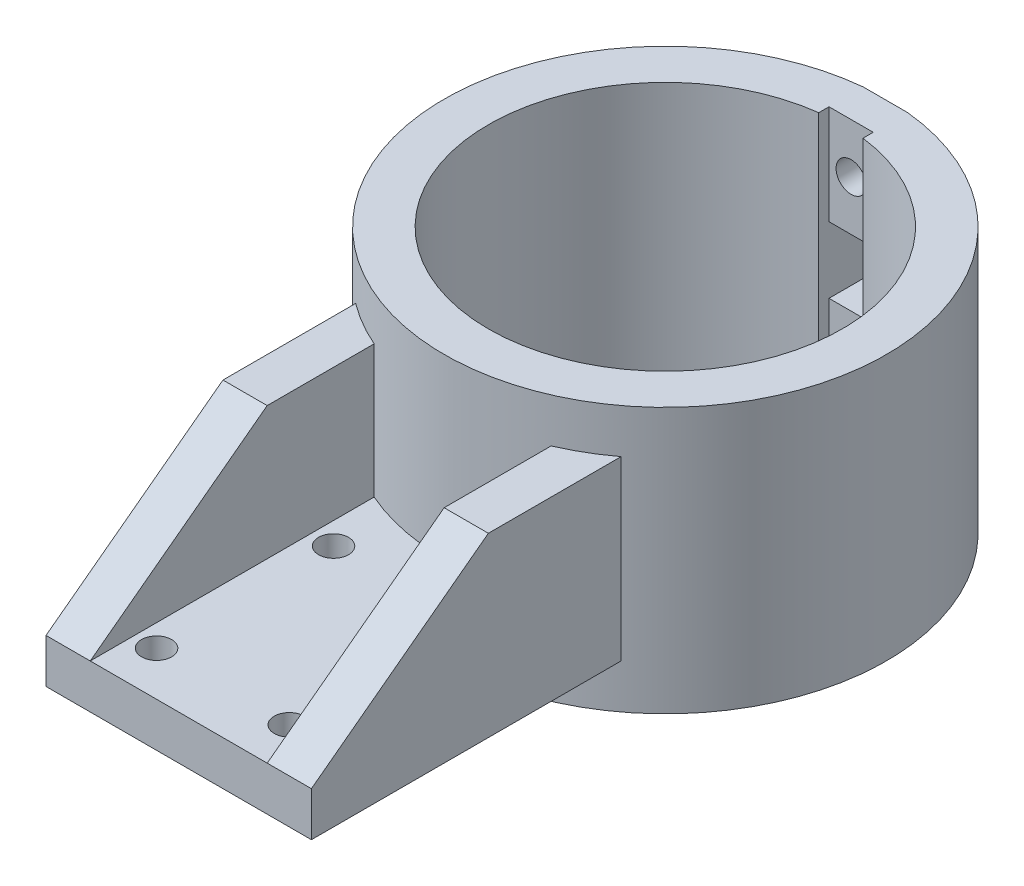
SolidWorks part; units mm, degrees
material "AISI 304"
ref_plane "前视基准面" through (0, 0, 0) normal (0, 0, 1) x (1, 0, 0)
ref_plane "上视基准面" through (0, 0, 0) normal (0, 1, 0) x (1, 0, 0)
ref_plane "右视基准面" through (0, 0, 0) normal (1, 0, 0) x (0, 0, -1)
ref_plane "Plane1" through (0, 0, 50) normal (0, 0, 1) x (1, 0, 0)
sketch "Sketch1" plane through (0, 0, 0) normal (0, 1, 0) x (1, 0, 0)
  circle A0 centre (0, 0) radius 50
  circle A1 centre (0, 0) radius 40
  dimension "D1" = 80
  dimension "D2" = 100
extrude "Extrude1" add sketch "Sketch1" along normal blind 60
sketch "Sketch2" plane through (0, 0, 50) normal (0, 0, 1) x (1, 0, 0)
  line L5 (-30, 50) -> (-20, 50)
  line L6 (30, 10) -> (-30, 10)
  line L7 (30, 10) -> (30, 50)
  line L9 (-30, 10) -> (-30, 50)
  line L10 (30, 10) -> (-30, 50) construction
  line L11 (30, 50) -> (-30, 10) construction
  line L16 (-20, 50) -> (-20, 20)
  line L17 (-20, 20) -> (20, 20)
  line L18 (20, 20) -> (20, 50)
  line L19 (20, 50) -> (30, 50)
  point P11 (0, 30)
  point P16 (0, 30)
  dimension "D1" = 60
  dimension "D2" = 10
  dimension "D3" = 40
  dimension "D4" = 10
  dimension "D5" = 10
extrude "Extrude2" add sketch "Sketch2" against normal up to body separate body
sketch "Sketch7" plane through (0, 0, 50) normal (0, 0, 1) x (1, 0, 0)
  line L20 (20, 20) -> (0, 20)
  line L21 (0, 20) -> (-20, 20)
  line L22 (-20, 20) -> (-20, 50)
  line L23 (-20, 50) -> (-30, 50)
  line L24 (-30, 50) -> (-30, 10)
  line L25 (-30, 10) -> (0, 10)
  line L26 (0, 10) -> (30, 10)
  line L27 (30, 10) -> (30, 50)
  line L28 (30, 50) -> (20, 50)
  line L29 (20, 50) -> (20, 20)
  line L30 (20, 20) -> (0, 20)
  line L31 (0, 20) -> (-20, 20)
  line L32 (-20, 20) -> (-20, 50)
  line L33 (-20, 50) -> (-30, 50)
  line L34 (-30, 50) -> (-30, 10)
  line L35 (-30, 10) -> (0, 10)
  line L36 (0, 10) -> (30, 10)
  line L37 (30, 10) -> (30, 50)
  line L38 (30, 50) -> (20, 50)
  line L39 (20, 50) -> (20, 20)
  dimension "D1" = 0
sketch "Sketch8" plane through (0, 0, 50) normal (0, 0, 1) x (1, 0, 0)
  line L20 (20, 20) -> (0, 20)
  line L21 (0, 20) -> (-20, 20)
  line L22 (-20, 20) -> (-20, 50)
  line L23 (-20, 50) -> (-30, 50)
  line L24 (-30, 50) -> (-30, 10)
  line L25 (-30, 10) -> (0, 10)
  line L26 (0, 10) -> (30, 10)
  line L27 (30, 10) -> (30, 50)
  line L28 (30, 50) -> (20, 50)
  line L29 (20, 50) -> (20, 20)
  line L30 (20, 20) -> (0, 20)
  line L31 (0, 20) -> (-20, 20)
  line L32 (-20, 20) -> (-20, 50)
  line L33 (-20, 50) -> (-30, 50)
  line L34 (-30, 50) -> (-30, 10)
  line L35 (-30, 10) -> (0, 10)
  line L36 (0, 10) -> (30, 10)
  line L37 (30, 10) -> (30, 50)
  line L38 (30, 50) -> (20, 50)
  line L39 (20, 50) -> (20, 20)
  dimension "D1" = 0
extrude "Extrude5" add sketch "Sketch8" along normal blind 60
sketch "Sketch9" plane through (-30, 0, 0) normal (-1, 0, 0) x (0, 0, 1)
  line L0 (110, 50) -> (110, 20)
  line L1 (110, 20) -> (70, 50)
  line L2 (40, 50) -> (110, 50) construction
  line L3 (70, 50) -> (110, 50)
  dimension "D1" = 40
extrude "Extrude6" cut sketch "Sketch9" against normal through all both and the other way through all
sketch "Sketch10" plane through (0, 60, 0) normal (0, 1, 0) x (1, 0, 0)
  line L0 (0, 54.1331) -> (0, -107.2527) construction
  line L2 (-5, 42) -> (5, 42)
  line L3 (-5, 42) -> (-5, 38)
  line L4 (-5, 38) -> (5, 38)
  line L5 (5, 42) -> (5, 38)
  line L6 (-5, 42) -> (5, 38) construction
  line L7 (-5, 38) -> (5, 42) construction
  line L8 (5, 50.2506) -> (-5, 50.2506)
  line L9 (5, 50.2506) -> (5, 49.7494)
  line L10 (5, 49.7494) -> (-5, 49.7494)
  line L11 (-5, 50.2506) -> (-5, 49.7494)
  line L12 (5, 50.2506) -> (-5, 49.7494) construction
  line L13 (5, 49.7494) -> (-5, 50.2506) construction
  circle A0 centre (0, 0) radius 40 construction
  circle A1 centre (0, 0) radius 50 construction
  point P3 (0, 40)
  point P10 (0, 50)
  dimension "D1" = 10
  dimension "D2" = 10
  dimension "D3" = 4
extrude "Extrude7" cut sketch "Sketch10" against normal through all
sketch "Sketch11" plane through (0, 0, -49.7494) normal (0, 0, -1) x (-1, 0, 0)
  line L0 (-5, 0) -> (-5, 60) construction
  line L1 (-5, 37.5) -> (5, 37.5)
  line L2 (-5, 37.5) -> (-5, 22.5)
  line L3 (-5, 22.5) -> (5, 22.5)
  line L4 (5, 37.5) -> (5, 22.5)
  line L5 (5, 0) -> (5, 60) construction
  line L6 (-50, 30) -> (50, 30) construction
  line L7 (-50, 60) -> (-50, 0) construction
  line L8 (50, 0) -> (50, 60) construction
  dimension "D1" = 15
  dimension "D2" = 7.5
extrude "Extrude8" cut sketch "Sketch11" against normal up to next
sketch "Sketch13" plane through (0, 0, -49.7494) normal (0, 0, -1) x (-1, 0, 0)
  line L0 (0, 60) -> (0, 0) construction
  line L1 (5, 60) -> (-5, 60) construction
  line L3 (5, 0) -> (-5, 0) construction
  point P5 (0, 48.75)
  point P6 (0, 11.25)
  dimension "D1" = 11.25
  dimension "D2" = 11.25
hole_wizard "M8 Tapped Hole2" positions "3DSketch3" profile "Sketch14" tap size "M8" standard "GB"
sketch3d "3DSketch3"
  point P0 (0, 48.75, -49.7494)
  point P3 (0, 11.25, -49.7494)
sketch "Sketch14" plane through (0, 48.75, -49.7494) normal (1, 0, 0) x (0, 1, 0)
  line L0 (0, 0) -> (0, 21.7929)
  line L1 (0, 21.7929) -> (3.4, 19.75)
  line L2 (3.4, 19.75) -> (3.4, 0)
  line L5 (3.4, 0) -> (0, 0)
  line L10 (0, 21.7929) -> (-3.4, 19.75) construction
  line L11 (0, -6.35) -> (0, 107.95) construction
  dimension "螺纹孔钻头直径" = 6.8
  dimension "螺纹孔钻头深度" = 19.75
  dimension "导头角度" = 118
cosmetic thread "Cosmetic Thread1" parameters "D1"=9.0977, "D2"=8
cosmetic thread "Cosmetic Thread2" parameters "D1"=9.0977, "D2"=8
sketch "Sketch15" plane through (0, 20, 0) normal (0, 1, 0) x (1, 0, 0)
  line L0 (0, -110) -> (0, -50) construction
  line L1 (20, -110) -> (-20, -110) construction
  line L2 (0, -50) -> (30, -50) construction
  line L3 (-15, -80) -> (15, -80) construction
  line L4 (15, -100) -> (-15, -100) construction
  line L5 (15, -100) -> (15, -60) construction
  line L6 (15, -60) -> (-15, -60) construction
  line L7 (-15, -100) -> (-15, -60) construction
  line L8 (15, -100) -> (-15, -60) construction
  line L9 (15, -60) -> (-15, -100) construction
  arc A0 (-5, 49.7494) -> (5, 49.7494) centre (0, 0) ccw construction
  point P7 (0, -80)
  dimension "D1" = 30
  dimension "D2" = 40
  dimension "D3" = 80
hole_wizard "M8 Tapped Hole3" positions "3DSketch4" profile "Sketch16" tap size "M8" standard "GB"
sketch3d "3DSketch4"
  point P0 (-15, 20, 60)
  point P3 (15, 20, 60)
  point P6 (-15, 20, 100)
  point P9 (15, 20, 100)
sketch "Sketch16" plane through (-15, 20, 60) normal (1, 0, 0) x (0, 0, 1)
  line L0 (0, 0) -> (0, 21.7929)
  line L1 (0, 21.7929) -> (3.4, 19.75)
  line L2 (3.4, 19.75) -> (3.4, 0)
  line L5 (3.4, 0) -> (0, 0)
  line L10 (0, 21.7929) -> (-3.4, 19.75) construction
  line L11 (0, -6.35) -> (0, 107.95) construction
  dimension "螺纹孔钻头直径" = 6.8
  dimension "螺纹孔钻头深度" = 19.75
  dimension "导头角度" = 118
cosmetic thread "Cosmetic Thread3" parameters "D1"=10, "D2"=8
cosmetic thread "Cosmetic Thread4" parameters "D1"=10, "D2"=8
cosmetic thread "Cosmetic Thread5" parameters "D1"=10, "D2"=8
cosmetic thread "Cosmetic Thread6" parameters "D1"=10, "D2"=8
